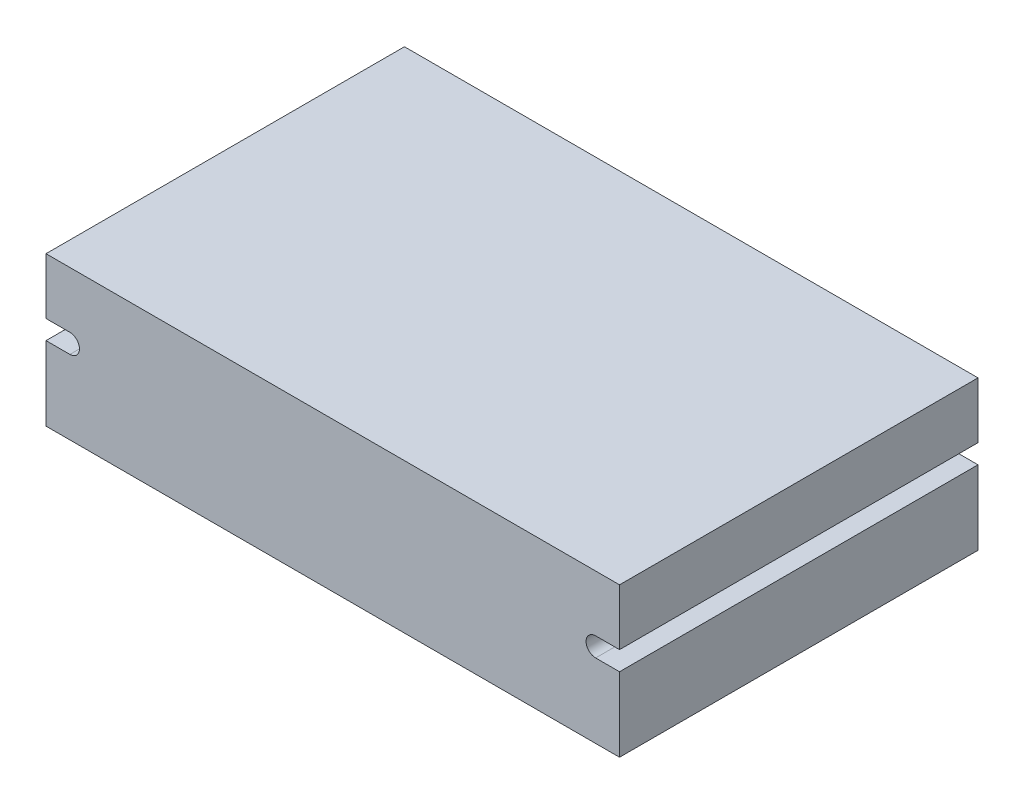
SolidWorks part; units mm, degrees
ref_plane "Piano frontale" through (0, 0, 0) normal (0, 0, 1) x (1, 0, 0)
ref_plane "Piano superiore" through (0, 0, 0) normal (0, 1, 0) x (1, 0, 0)
ref_plane "Piano destro" through (0, 0, 0) normal (1, 0, 0) x (0, 0, -1)
sketch "Schizzo1" plane through (0, 0, 0) normal (0, 0, 1) x (1, 0, 0)
  line L0 (-16.1123, 14) -> (105.4911, 14) construction
  line L1 (0, 0) -> (96, 0)
  line L2 (0, 0) -> (0, 12.3987)
  line L3 (0, 25) -> (96, 25)
  line L4 (96, 0) -> (96, 12.3987)
  line L5 (-4, 14) -> (4, 14) construction
  line L6 (0, 15.6013) -> (4, 15.6013)
  line L7 (0, 12.3987) -> (4, 12.3987)
  line L8 (48, 25) -> (48, 0) construction
  line L9 (0, 15.6013) -> (0, 25)
  line L10 (96, 12.3987) -> (92, 12.3987)
  line L11 (96, 15.6013) -> (92, 15.6013)
  line L12 (96, 15.6013) -> (96, 25)
  arc A0 (92, 12.3987) -> (92, 15.6013) centre (92, 14) cw
  arc A1 (4, 12.3987) -> (4, 15.6013) centre (4, 14) ccw
  point P6 (0, 14)
  point P21 (96, 14)
  dimension "D3" = 4
  dimension "D1" = 25
  dimension "D2" = 96
extrude "Estrusione-Estrusione1" add sketch "Schizzo1" along normal blind 60
